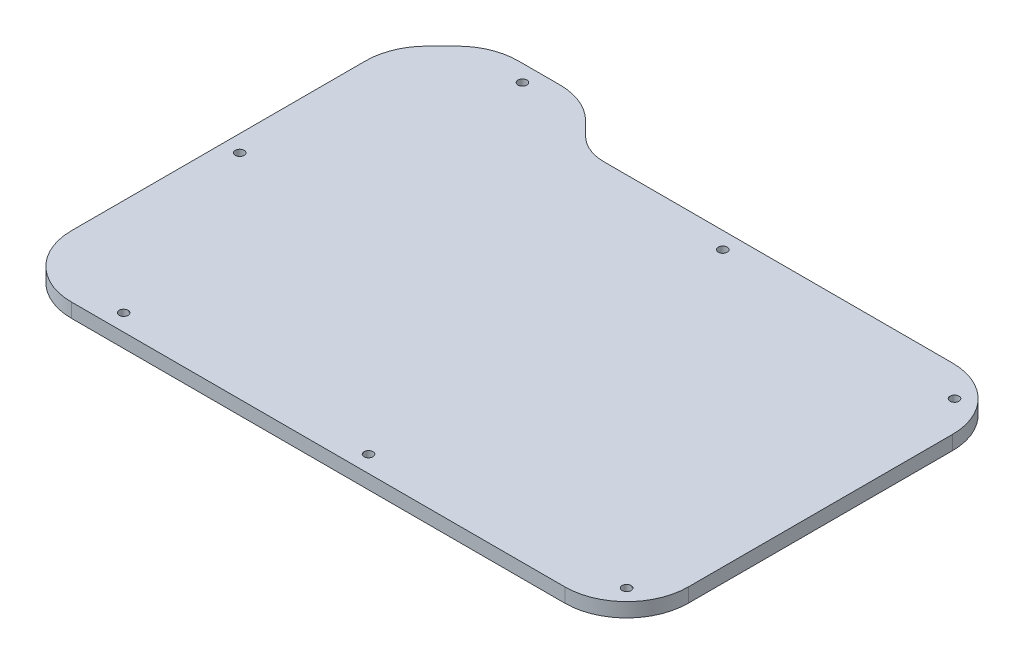
SolidWorks part; units mm, degrees
ref_plane "Front Plane" through (0, 0, 0) normal (0, 0, 1) x (1, 0, 0)
ref_plane "Top Plane" through (0, 0, 0) normal (0, 1, 0) x (1, 0, 0)
ref_plane "Right Plane" through (0, 0, 0) normal (1, 0, 0) x (0, 0, -1)
sketch "Sketch1" plane through (0, 0, 0) normal (0, 1, 0) x (1, 0, 0)
  line L21 (-268.2537, -101.0569) -> (-268.2537, -167.0766)
  line L22 (-254.4037, -180.9266) -> (-143.6689, -180.9266)
  line L23 (-129.8189, -167.0766) -> (-129.8189, -107.7766)
  line L24 (-143.6689, -93.9266) -> (-221.8815, -93.9266)
  line L27 (-241.7605, -83.9266) -> (-251.1235, -83.9266)
  line L28 (-260.9169, -87.9832) -> (-264.1972, -91.2634)
  line L29 (-231.967, -87.9832) -> (-228.9526, -90.9977)
  circle A35 centre (-246.442, -177.1766) radius 1
  circle A36 centre (-264.5037, -133.0668) radius 1
  circle A37 centre (-246.442, -87.6766) radius 1
  circle A38 centre (-191.4845, -97.6766) radius 1
  circle A39 centre (-136.5271, -100.6348) radius 1
  circle A40 centre (-136.5271, -174.2184) radius 1
  circle A41 centre (-191.4845, -177.1766) radius 1
  arc A42 (-268.2537, -167.0766) -> (-254.4037, -180.9266) centre (-254.4037, -167.0766) ccw
  arc A43 (-143.6689, -180.9266) -> (-129.8189, -167.0766) centre (-143.6689, -167.0766) ccw
  arc A44 (-129.8189, -107.7766) -> (-143.6689, -93.9266) centre (-143.6689, -107.7766) ccw
  arc A46 (-231.967, -87.9832) -> (-241.7605, -83.9266) centre (-241.7605, -97.7766) ccw
  arc A47 (-251.1235, -83.9266) -> (-260.9169, -87.9832) centre (-251.1235, -97.7766) ccw
  arc A48 (-264.1972, -91.2634) -> (-268.2537, -101.0569) centre (-254.4037, -101.0569) ccw
  arc A49 (-221.8815, -93.9266) -> (-228.9526, -90.9977) centre (-221.8815, -83.9266) cw
  dimension "D1" = 10
extrude "Boss-Extrude1" add sketch "Sketch1" along normal blind 3.175
